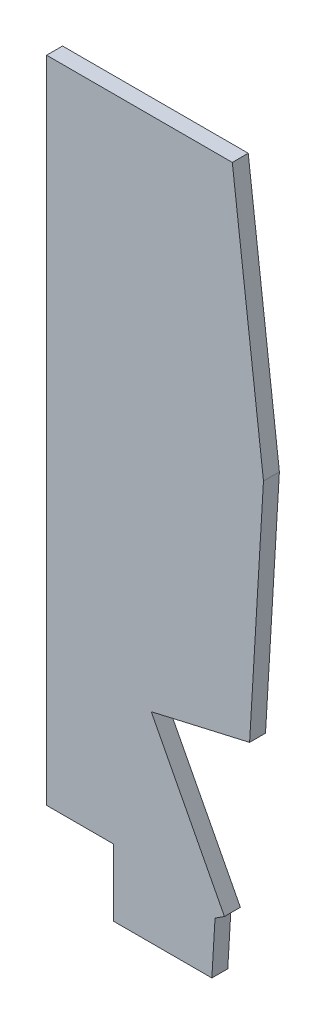
SolidWorks part; units mm, degrees
ref_plane "Front Plane" through (0, 0, 0) normal (0, 0, 1) x (1, 0, 0)
ref_plane "Top Plane" through (0, 0, 0) normal (0, 1, 0) x (1, 0, 0)
ref_plane "Right Plane" through (0, 0, 0) normal (1, 0, 0) x (0, 0, -1)
sketch "Sketch1" plane through (0, 0, 0) normal (0, 0, 1) x (1, 0, 0)
  line L1 (-100, 112.5) -> (100, 112.5)
  line L2 (-100, 112.5) -> (-100, -112.5)
  line L3 (-100, -112.5) -> (100, -112.5)
  line L4 (100, 112.5) -> (100, -112.5)
  line L5 (-100, 112.5) -> (100, -112.5) construction
  line L6 (-100, -112.5) -> (100, 112.5) construction
  point P0 (0, 0)
  dimension "D1" = 200
  dimension "D2" = 225
extrude "Boss-Extrude1" add sketch "Sketch1" along normal blind 5
sketch "Sketch2" plane through (0, 0, 5) normal (0, 0, 1) x (1, 0, 0)
  line L1 (-100, -112.5) -> (-79, -112.5)
  line L2 (-100, -112.5) -> (-100, -91.5)
  line L3 (-100, -91.5) -> (-79, -91.5)
  line L4 (-79, -112.5) -> (-79, -91.5)
  dimension "D1" = 21
  dimension "D2" = 21
extrude "Cut-Extrude1" cut sketch "Sketch2" against normal through all
sketch "Sketch3" plane through (0, 0, 5) normal (0, 0, 1) x (1, 0, 0)
  line L0 (-47.1151, -95.7121) -> (-48.1143, -112.5)
  line L2 (-47.1151, -95.7121) -> (-44.1551, -93.7987)
  line L3 (-44.1551, -93.7987) -> (-67.1448, -49.5963)
  line L4 (-67.1448, -49.5963) -> (-36.263, -42.505)
  line L5 (-36.263, -42.505) -> (-31.9027, 30.7544)
  line L6 (-31.9027, 30.7544) -> (-41.689, 112.5)
  line L7 (100, 112.5) -> (-100, 112.5) construction
  line L8 (-79, -112.5) -> (100, -112.5) construction
  line L9 (100, -112.5) -> (100, 112.5) construction
  line L10 (100, 112.5) -> (-41.689, 112.5)
  line L11 (100, -112.5) -> (100, 112.5)
  line L12 (-48.1143, -112.5) -> (100, -112.5)
extrude "Cut-Extrude2" cut sketch "Sketch3" against normal through all
